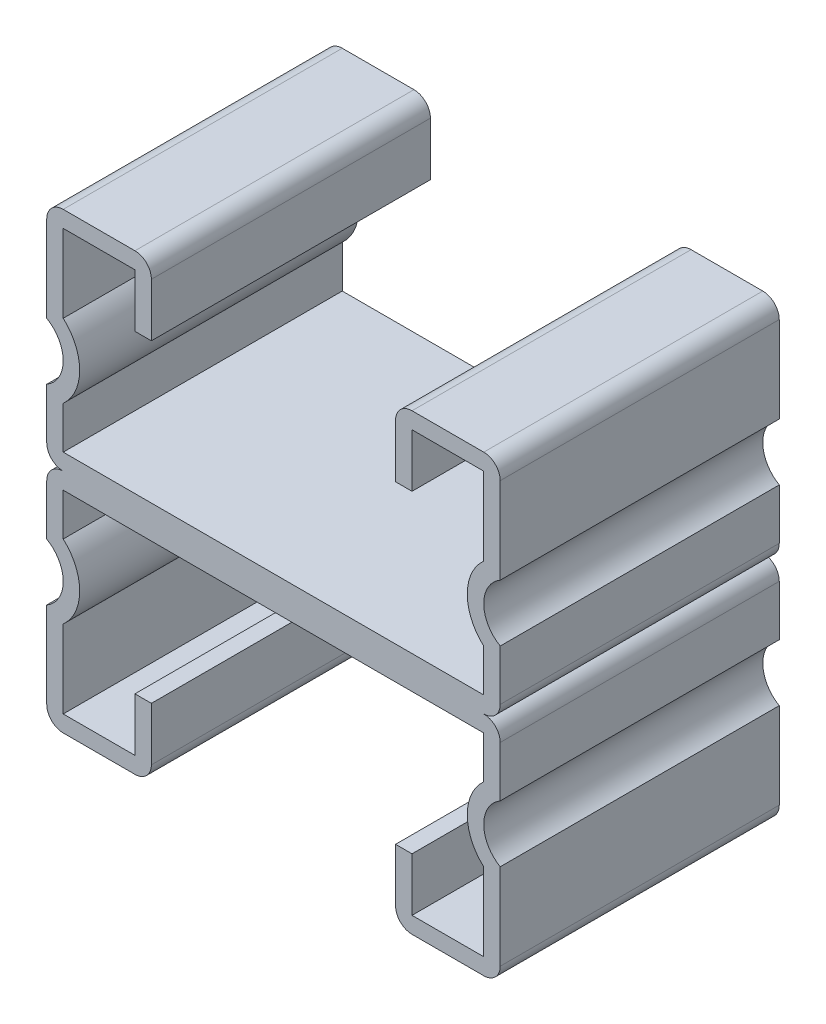
SolidWorks part; units mm, degrees
ref_plane "Plane1" through (0, 0, 0) normal (0, 0, 1) x (1, 0, 0)
ref_plane "Plane2" through (0, 0, 0) normal (0, 1, 0) x (1, 0, 0)
ref_plane "Plane3" through (0, 0, 0) normal (1, 0, 0) x (0, 0, -1)
sketch "Sketch1" plane through (0, 0, 0) normal (0, 0, 1) x (1, 0, 0)
  line L0 (-20.6375, 19.1389) -> (-20.6375, 11.2952)
  line L1 (-20.6375, 6.1038) -> (-20.6375, 1.4986)
  line L2 (-19.1389, 0) -> (19.1389, 0)
  line L3 (20.6375, 1.4986) -> (20.6375, 6.1038)
  line L4 (20.6375, 11.2952) -> (20.6375, 19.1389)
  line L5 (19.1389, 20.6375) -> (12.6111, 20.6375)
  line L6 (11.1125, 19.1389) -> (11.1125, 14.2875)
  line L7 (-19.1389, 20.6375) -> (-12.6111, 20.6375)
  line L8 (-11.1125, 19.1389) -> (-11.1125, 14.2875)
  line L9 (19.1389, 3.4236) -> (19.1389, 6.4516) construction
  line L10 (-19.1389, 15.1511) -> (-19.1389, 3.4236) construction
  line L11 (-12.6111, 19.1389) -> (-12.6111, 14.2875)
  line L12 (-19.1389, 19.1389) -> (-12.6111, 19.1389)
  line L13 (-19.1389, 19.1389) -> (-19.1389, 12.0505)
  line L14 (-19.1389, 5.3485) -> (-19.1389, 1.4986)
  line L15 (-19.1389, 1.4986) -> (19.1389, 1.4986)
  line L16 (19.1389, 1.4986) -> (19.1389, 5.3485)
  line L17 (19.1389, 12.0505) -> (19.1389, 19.1389)
  line L18 (19.1389, 19.1389) -> (12.6111, 19.1389)
  line L19 (12.6111, 19.1389) -> (12.6111, 14.2875)
  line L20 (-12.6111, 14.2875) -> (-11.1125, 14.2875)
  line L21 (11.1125, 14.2875) -> (12.6111, 14.2875)
  arc A0 (20.6375, 11.2952) -> (20.6375, 6.1038) centre (22.1361, 8.6995) ccw
  arc A1 (-20.6375, 6.1038) -> (-20.6375, 11.2952) centre (-22.1361, 8.6995) ccw
  arc A2 (-12.6111, 20.6375) -> (-11.1125, 19.1389) centre (-12.6111, 19.1389) cw
  arc A3 (-20.6375, 19.1389) -> (-19.1389, 20.6375) centre (-19.1389, 19.1389) cw
  arc A4 (-19.1389, 0) -> (-20.6375, 1.4986) centre (-19.1389, 1.4986) cw
  arc A5 (20.6375, 1.4986) -> (19.1389, 0) centre (19.1389, 1.4986) cw
  arc A6 (19.1389, 20.6375) -> (20.6375, 19.1389) centre (19.1389, 19.1389) cw
  arc A7 (11.1125, 19.1389) -> (12.6111, 20.6375) centre (12.6111, 19.1389) cw
  arc A8 (-19.1389, 5.3485) -> (-19.1389, 12.0505) centre (-22.1361, 8.6995) ccw
  arc A9 (19.1389, 12.0505) -> (19.1389, 5.3485) centre (22.1361, 8.6995) ccw
  dimension "D9" = 2.9972
  dimension "D10" = 2.9972
  dimension "Width" = 41.275
  dimension "D6" = 22.225
  dimension "edge" = 9.525
  dimension "Lip" = 6.35
  dimension "D1" = 20.6375
  dimension "D2" = 8.6995
  dimension "gauge" = 1.4986
extrude "Base-Extrude" add sketch "Sketch1" along normal mid plane 25.4
mirror "Mirror1" about plane through (0, 0, 0) normal (0, 1, 0) of "Base-Extrude"
equation "\"D1@Sketch1\" = \"Width@Sketch1\" / 2"
equation "\"D6@Sketch1\" = \"Width@Sketch1\" - 2 * \"edge@Sketch1\""
equation "\"D10@Sketch1\" = 2 * \"gauge@Sketch1\""
equation "\"D9@Sketch1\" = \"D10@Sketch1\""
